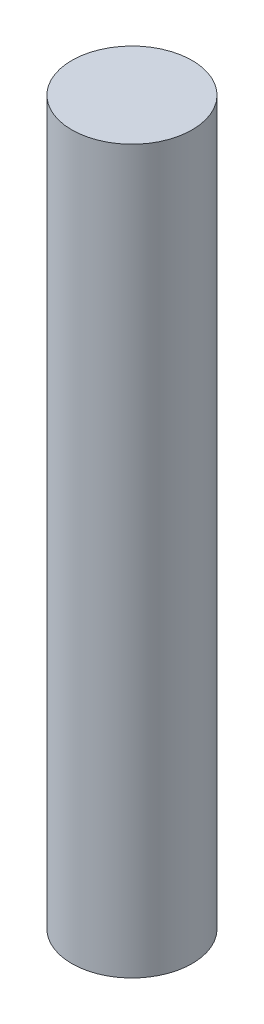
SolidWorks part; units mm, degrees
ref_plane "前视基准面" through (0, 0, 0) normal (0, 0, 1) x (1, 0, 0)
ref_plane "上视基准面" through (0, 0, 0) normal (0, 1, 0) x (1, 0, 0)
ref_plane "右视基准面" through (0, 0, 0) normal (1, 0, 0) x (0, 0, -1)
sketch "草图1" plane through (0, 0, 0) normal (0, 1, 0) x (1, 0, 0)
  circle A0 centre (0, 0) radius 2.5
extrude "凸台-拉伸1" add sketch "草图1" along normal blind 30
